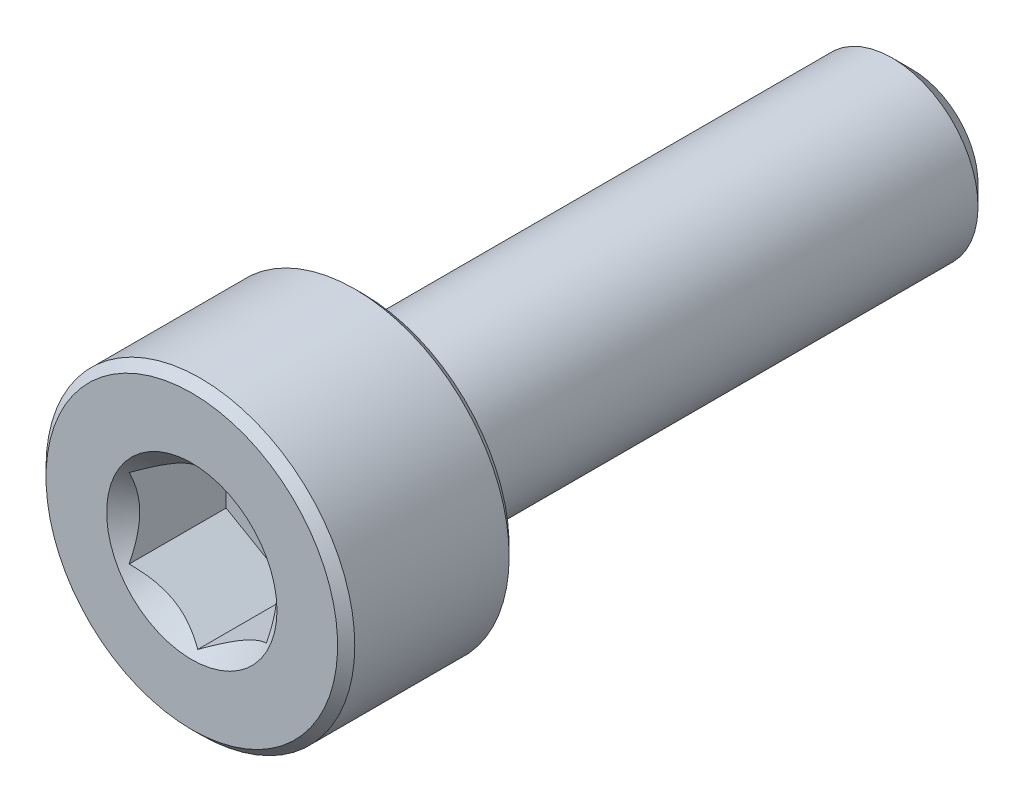
SolidWorks part; units mm, degrees
ref_plane "Front Plane" through (0, 0, 0) normal (0, 0, 1) x (1, 0, 0)
ref_plane "Top Plane" through (0, 0, 0) normal (0, 1, 0) x (1, 0, 0)
ref_plane "Right Plane" through (0, 0, 0) normal (1, 0, 0) x (0, 0, -1)
sketch "Sketch1" plane through (0, 0, 0) normal (1, 0, 0) x (0, 0, -1)
  line L0 (-5.25, 0) -> (5.25, 0) construction
  line L1 (5.25, 0) -> (5.25, 0.9577) construction
  line L2 (5.25, 0.9577) -> (4.9577, 1.25) construction
  line L3 (4.9577, 1.25) -> (4.9125, 1.25) construction
  line L4 (4.9125, 1.25) -> (-2.75, 1.25) construction
  line L5 (-2.75, 1.25) -> (-2.75, 2.25) construction
  line L6 (-2.75, 2.25) -> (-5.25, 2.25) construction
  line L7 (-5.25, 2.25) -> (-5.25, 0) construction
  line L8 (5.25, 0.9577) -> (5.25, 1.25) construction
  line L9 (5.2219, 1.2987) -> (5.4469, 0.909) construction
  line L10 (5.4469, 0.909) -> (5.6719, 1.2987) construction
  line L11 (5.6719, 1.2987) -> (5.2219, 1.2987) construction
  line L12 (5.4469, 1.2987) -> (5.4469, 1.25) construction
  line L13 (5.4469, 0.909) -> (5.4469, 0.9577) construction
  line L14 (5.4187, 0.9577) -> (5.475, 0.9577) construction
  line L15 (5.25, 1.25) -> (5.6437, 1.25) construction
  line L16 (5.2359, 1.2744) -> (5.6578, 1.2744) construction
  line L17 (5.25, 0) -> (5.25, -1.25) construction
  line L18 (-2.875, 2.25) -> (-2.75, 2.125) construction
  line L19 (-5.125, 2.25) -> (-5.25, 2.125) construction
  line L20 (-2.75, 1.25) -> (-2.75, 0) construction
  line L21 (-2.75, 0.625) -> (-0.0833, 0.625) construction
  line L22 (-0.0833, 0.625) -> (2.5833, 0.625) construction
  line L23 (2.5833, 0.625) -> (5.25, 0.625) construction
  line L24 (-0.0833, 0.625) -> (-0.0833, 1.25) construction
  line L25 (-0.0833, 1.25) -> (-0.0833, 2.25) construction
  line L26 (2.5833, 0.625) -> (2.5833, 2.25) construction
  point P0 (-5.25, 1)
  point P3 (4.125, 1.25)
  point P4 (0, 0)
  point P18 (2.5833, 1.25)
  point P22 (5.4469, 0.9577)
  point P24 (4.9125, 1.25)
  point P25 (5.4469, 1.25)
  point P28 (5.4469, 1.2744)
  point P29 (4.125, -1.25)
  point P30 (-0.0833, 1.25)
  point P31 (-4, 2.25)
  point P37 (-3.1875, 2.25)
  point P38 (-5.0625, 2.25)
  point P45 (-0.0833, 0.625)
  point P46 (2.5833, 0.625)
  dimension "D2" = 0.0563
  dimension "D7" = 0.125
  dimension "D8" = 0.125
  dimension "D9" = 0.125
  dimension "D10" = 0.0625
  dimension "D11" = 0.3125
  dimension "Drive Size" = 2
  dimension "Head Diameter" = 4.5
  dimension "Head Height" = 2.5
  dimension "Thread Pitch" = 0.45
  dimension "Thread Dia" = 2.5
  dimension "Length" = 8
  dimension "D12" = 0.3375
  dimension "D4" = 1.125
  dimension "D3" = 45
sketch "Sketch2" plane through (0, 0, 0) normal (1, 0, 0) x (0, 0, -1)
  line L0 (-5.25, 0) -> (-5.25, 2.125)
  line L1 (-5.125, 2.25) -> (-2.875, 2.25)
  line L2 (-2.75, 2.125) -> (-2.75, 1.375)
  line L4 (4.9577, 1.25) -> (5.25, 0.9577)
  line L5 (5.25, 0.9577) -> (5.25, 0)
  line L6 (-2.75, 2.25) -> (-5.25, 2.25) construction
  line L7 (5.25, 0) -> (-5.25, 0)
  line L8 (-5.125, 2.25) -> (-5.25, 2.125) construction
  line L10 (-5.125, 2.25) -> (-5.25, 2.125)
  line L14 (-2.875, 2.25) -> (-2.75, 2.125) construction
  line L16 (-2.875, 2.25) -> (-2.75, 2.125)
  line L17 (-2.75, 1.25) -> (-2.75, 2.25) construction
  line L19 (-2.625, 1.25) -> (4.9577, 1.25)
  line L20 (4.9125, 1.25) -> (-2.75, 1.25) construction
  arc A1 (-2.75, 1.375) -> (-2.625, 1.25) centre (-2.625, 1.375) ccw
  dimension "D3" = 0.125
revolve "Revolve1" add sketch "Sketch2" angle 360 about L7
sketch "Sketch3" plane through (0, 0, 5.25) normal (0, 0, 1) x (1, 0, 0)
  line L1 (1, -0.5774) -> (1, 0.5774)
  line L2 (1, 0.5774) -> (0, 1.1547)
  line L3 (0, 1.1547) -> (-1, 0.5774)
  line L4 (-1, 0.5774) -> (-1, -0.5774)
  line L5 (-1, -0.5774) -> (0, -1.1547)
  line L6 (0, -1.1547) -> (1, -0.5774)
  circle A0 centre (0, 0) radius 1 construction
  circle A1 centre (0, 0) radius 2.25 construction
  circle A2 centre (0, 0) radius 2.25 construction
  circle A3 centre (0, 0) radius 1.1547 construction
  point P13 (0, 0)
  dimension "D1" = 2.3094
extrude "Cut-Extrude1" cut sketch "Sketch3" against normal offset from surface (1.5 mm away) 1 up to face at (0, 2.125, 2.75)
sketch "Sketch4" plane through (0, 0, 5.25) normal (0, 0, 1) x (1, 0, 0)
  circle A0 centre (0, 0) radius 1.2413
  dimension "D1" = 2.4826
extrude "Cut-Extrude2" cut sketch "Sketch4" against normal up to vertex (1.25 mm away) draft 45 up to point (0, 2.25, 4)
sketch "Sketch11" plane through (0, 0, 0) normal (1, 0, 0) x (0, 0, -1)
  line L0 (-5.25, 0) -> (5.25, 0) construction
  line L1 (-5.25, 0) -> (5.25, 0) construction
  line L2 (-1.25, 0) -> (-1.25, 1.25) construction
  line L3 (4.9125, 1.25) -> (-2.75, 1.25) construction
  line L4 (3.75, 0) -> (3.75, 1.25) construction
  line L6 (5.25, 0.9577) -> (5.25, 1.25) construction
  point P2 (-1.25, 0)
  point P3 (3.75, 0)
  dimension "D1" = 1.5
  dimension "D2" = 1.5
sketch "Sketch6" plane through (0, 0, -5.25) normal (0, 0, -1) x (-1, 0, 0)
  circle A0 centre (0, 0) radius 1.25
curve "Helix/Spiral1" pitch 0.45 height 8.45 turns 18.7778
sketch "Sketch10" plane through (0, 0, 0) normal (1, 0, 0) x (0, 0, -1)
  line L0 (-2.625, -2.25) -> (-2.625, 2.25)
  line L5 (-5.25, 0) -> (5.25, 0) construction
  line L6 (-2.625, 1.25) -> (-2.625, -1.25) construction
  point P3 (-2.625, 0)
split "Split1" trim tools "Sketch10" bodies to split 106 resulting bodies 114 115
sketch "Sketch8" plane through (0, 0, 0) normal (1, 0, 0) x (0, 0, -1)
  line L0 (-2.75, 0) -> (-2.75, 1.25)
  line L1 (-2.625, -1.25) -> (-2.625, 1.25) construction
  line L2 (-2.75, 1.25) -> (-2.625, 1.25)
  line L4 (-2.625, 1.25) -> (-1.9033, 0)
  line L5 (-1.9033, 0) -> (-2.75, 0)
  line L6 (4.9125, 1.25) -> (-2.75, 1.25) construction
  line L7 (-5.25, 0) -> (5.25, 0) construction
  dimension "D1" = 60
revolve "Revolve2" add sketch "Sketch8" angle 360 about L5
equation "\"D2@Sketch1\" = \"Thread Pitch@Sketch1\" / 8"
equation "\"D4@Helix/Spiral1\" = \"Thread Pitch@Sketch1\""
equation "\"D7@Sketch1\" = \"Head Height@Sketch1\" * .05"
equation "\"D8@Sketch1\"=\"D7@Sketch1\""
equation "\"D9@Sketch1\"=\"D7@Sketch1\""
equation "\"D10@Sketch1\"=\"D7@Sketch1\"/2"
equation "\"D11@Sketch1\"=\"D10@Sketch1\"*5"
equation "\"D4@Sketch1\"=\"Thread Pitch@Sketch1\"*2.5"
equation "\"D12@Sketch1\"=\"Thread Pitch@Sketch1\"*.75"
equation "\"D3@Helix/Spiral1\"=\"Length@Sketch1\"+\"Thread Pitch@Sketch1\""
equation "\"D3@Sketch2\"=\"Thread Dia@Sketch1\"*0.05"
equation "\"D1@Sketch11\"=\"Length@Sketch1\"*0.1875"
equation "\"D2@Sketch11\"=\"D1@Sketch11\""
equation "\"D1@Sketch4\"=\"D1@Sketch3\"*1.075"
